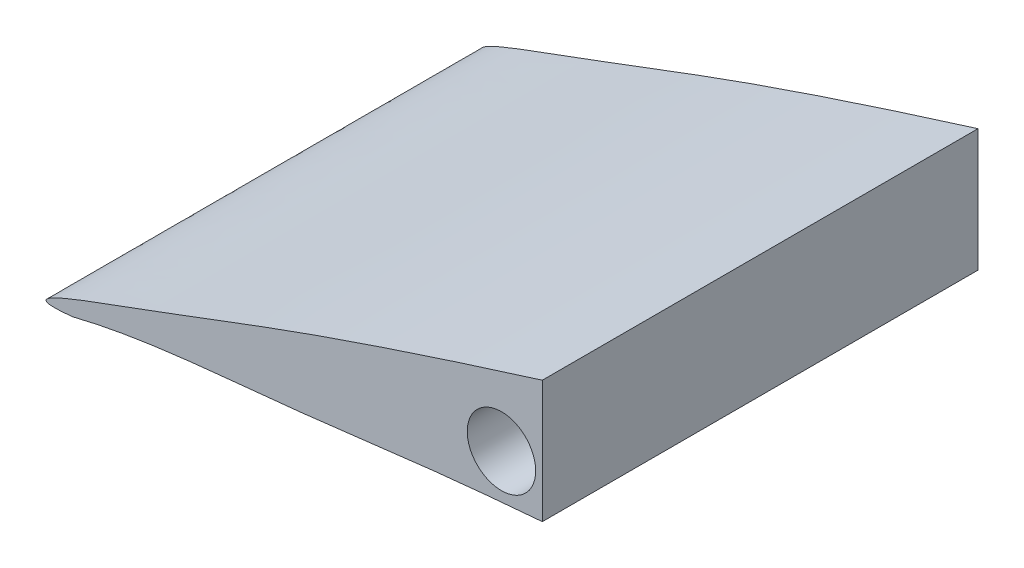
SolidWorks part; units mm, degrees
ref_plane "Front Plane" through (0, 0, 0) normal (0, 0, 1) x (1, 0, 0)
ref_plane "Top Plane" through (0, 0, 0) normal (0, 1, 0) x (1, 0, 0)
ref_plane "Right Plane" through (0, 0, 0) normal (1, 0, 0) x (0, 0, -1)
sketch "Sketch1" plane through (0, 0, 0) normal (0, 0, 1) x (1, 0, 0)
  line L0 (42.9183, -0.4477) -> (42.9183, 8.2631)
  circle A0 centre (-19.1025, -6.0109) radius 2.127
  circle A1 centre (12.6475, 4.4031) radius 2.127
  arc A2 (37.8951, -5.5274) -> (42.9183, -0.4477) centre (37.8383, -0.4477) ccw
  arc A3 (42.9183, 8.2631) -> (36.6811, 13.2095) centre (37.8383, 8.2631) ccw
  circle A4 centre (33.8935, 3.4217) radius 2.032
  spline S0 degree 3 poles (36.6811, 13.2095) (19.8298, 9.2672) (-2.0736, 3.8441) (-31.0965, -5.5459) (-39.3168, -8.8066) (-49.5156, -12.4957) (-45.7725, -12.1069) knots 0.118069 0.118069 0.118069 0.118069 0.630725 0.824214 0.940085 1 1 1 1
  spline S1 degree 3 poles (-45.7725, -12.1069) (-41.3374, -10.9993) (-33.8316, -10.53) (-20.4835, -8.7075) (-8.8734, -8.0192) (11.5246, -6.0282) (26.0673, -5.6598) (37.8951, -5.5274) knots 0 0 0 0 0.144322 0.237948 0.427123 0.512832 0.887818 0.887818 0.887818 0.887818
extrude "Boss-Extrude1" add sketch "Sketch1" along normal blind 27.0764
sketch "Sketch2" plane through (0, 0, 27.0764) normal (0, 0, 1) x (1, 0, 0)
  line L1 (-16.5625, 14.1188) -> (88.17, 14.1188)
  line L2 (-16.5625, 14.1188) -> (-16.5625, -18.8296)
  line L3 (-16.5625, -18.8296) -> (88.17, -18.8296)
  line L4 (88.17, 14.1188) -> (88.17, -18.8296)
  dimension "D1" = 29.21
extrude "Cut-Extrude1" cut sketch "Sketch2" against normal blind 27.0764
